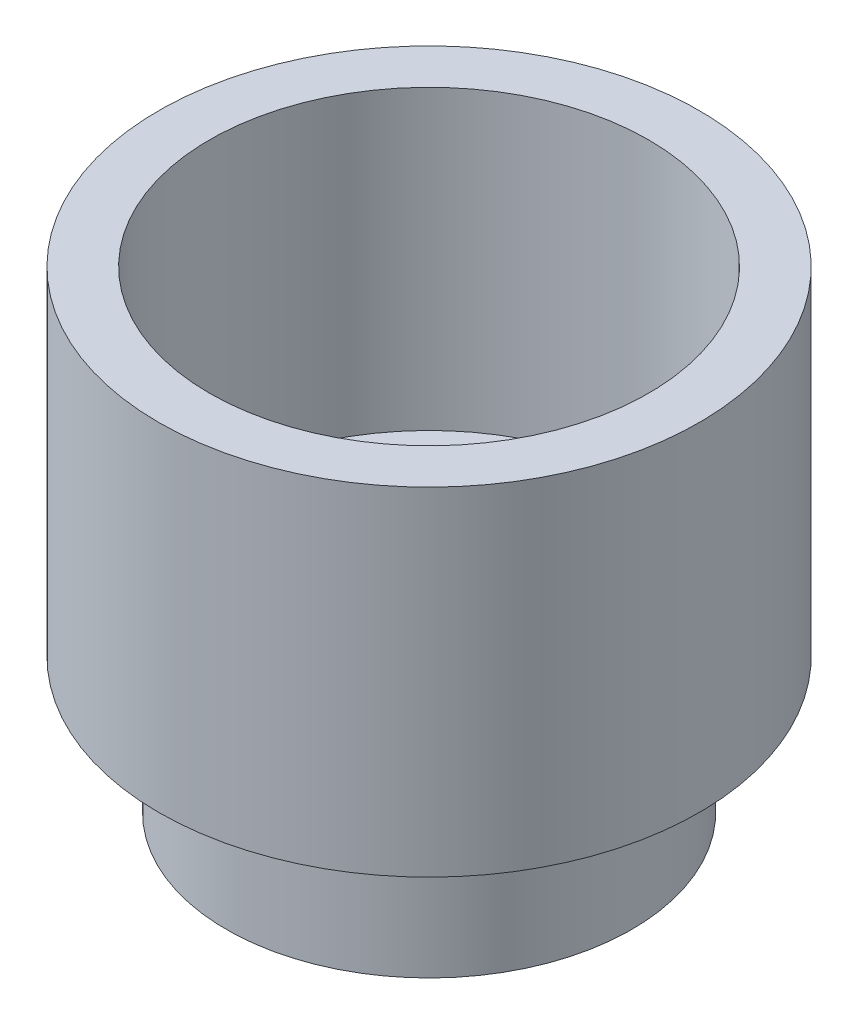
SolidWorks part; units mm, degrees
ref_plane "Front Plane" through (0, 0, 0) normal (0, 0, 1) x (1, 0, 0)
ref_plane "Top Plane" through (0, 0, 0) normal (0, 1, 0) x (1, 0, 0)
ref_plane "Right Plane" through (0, 0, 0) normal (1, 0, 0) x (0, 0, -1)
sketch "Sketch1" plane through (0, 0, 0) normal (0, 1, 0) x (1, 0, 0)
  circle A0 centre (0, 0) radius 5.08
  dimension "D1" = 10.16
extrude "Boss-Extrude1" add sketch "Sketch1" along normal blind 6.35
sketch "Sketch2" plane through (0, 6.35, 0) normal (0, 1, 0) x (1, 0, 0)
  circle A0 centre (0, 0) radius 4.1275
  dimension "D1" = 8.255
extrude "Cut-Extrude1" cut sketch "Sketch2" against normal blind 5.588
sketch "Sketch3" plane through (0, 0, 0) normal (0, -1, 0) x (1, 0, 0)
  circle A0 centre (0, 0) radius 3.81
  dimension "D1" = 7.62
extrude "Boss-Extrude2" add sketch "Sketch3" along normal blind 2.54
sketch "Sketch4" plane through (0, -2.54, 0) normal (0, -1, 0) x (1, 0, 0)
  circle A0 centre (0, 0) radius 2.54
  dimension "D1" = 5.08
extrude "Cut-Extrude2" cut sketch "Sketch4" against normal blind 2.54
